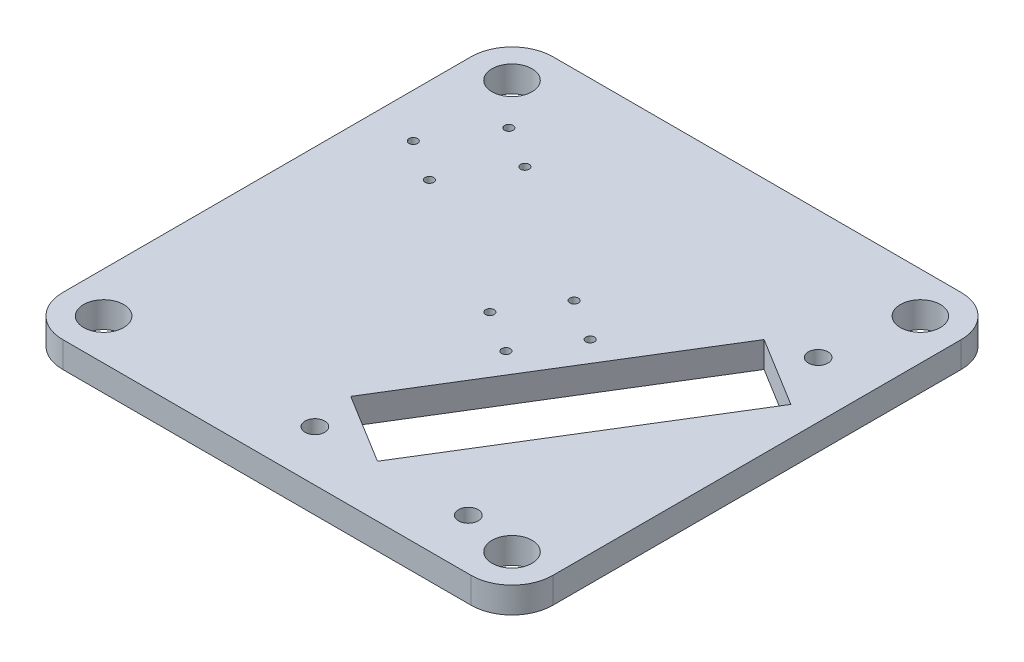
SolidWorks part; units mm, degrees
ref_plane "Front Plane" through (0, 0, 0) normal (0, 0, 1) x (1, 0, 0)
ref_plane "Top Plane" through (0, 0, 0) normal (0, 1, 0) x (1, 0, 0)
ref_plane "Right Plane" through (0, 0, 0) normal (1, 0, 0) x (0, 0, -1)
sketch "Sketch1" plane through (0, 0, 0) normal (0, 1, 0) x (1, 0, 0)
  line L1 (10, 0) -> (110, 0)
  line L2 (0, 10) -> (0, 110)
  line L3 (10, 120) -> (110, 120)
  line L4 (120, 10) -> (120, 110)
  arc A0 (110, 0) -> (120, 10) centre (110, 10) ccw
  arc A1 (10, 0) -> (0, 10) centre (10, 10) cw
  arc A2 (0, 110) -> (10, 120) centre (10, 110) cw
  arc A3 (110, 120) -> (120, 110) centre (110, 110) cw
  point P7 (120, 0)
  point P10 (0, 0)
  point P13 (0, 120)
  point P16 (120, 120)
  dimension "D3" = 10
  dimension "D1" = 120
  dimension "D2" = 120
extrude "Boss-Extrude1" add sketch "Sketch1" along normal blind 6.35
sketch "Sketch2" plane through (0, 6.35, 0) normal (0, 1, 0) x (1, 0, 0)
  line L0 (55.0317, 10) -> (99.0317, 10) construction
  line L1 (99.0317, 10) -> (110, 99.33) construction
  line L2 (110, 99.33) -> (55.0317, 10) construction
  line L3 (110, 120) -> (10, 120) construction
  line L4 (0, 110) -> (0, 10) construction
  line L5 (57.2915, 23.2132) -> (74.325, 12.7318)
  line L6 (74.325, 12.7318) -> (112.886, 75.398)
  line L7 (112.886, 75.398) -> (95.8525, 85.8794)
  line L8 (57.2915, 23.2132) -> (95.8525, 85.8794)
  line L9 (10, 0) -> (110, 0) construction
  line L10 (120, 10) -> (120, 110) construction
  circle A0 centre (59.3264, 12.4) radius 2.4
  circle A1 centre (96.9083, 12.4) radius 2.4
  circle A2 centre (106.2767, 88.6997) radius 2.4
  circle A3 centre (10, 110) radius 4.9
  circle A4 centre (10, 10) radius 4.9
  circle A5 centre (110, 110) radius 4.9
  circle A6 centre (110, 10) radius 4.9
  dimension "D6" = 4.8
  dimension "D7" = 4.8
  dimension "D8" = 4.8
  dimension "D14" = 9.8
  dimension "D15" = 9.8
  dimension "D16" = 9.8
  dimension "D17" = 9.8
  dimension "D20" = 10
  dimension "D1" = 97
  dimension "D2" = 44
  dimension "D3" = 89.33
  dimension "D4" = 10
  dimension "D5" = 10
  dimension "D9" = 20
  dimension "D10" = 73.58
  dimension "D11" = 5
  dimension "D12" = 7.865
  dimension "D13" = 8.1428
  dimension "D18" = 10
  dimension "D19" = 10
  dimension "D21" = 10
  dimension "D22" = 10
  dimension "D23" = 10
  dimension "D24" = 10
  dimension "D25" = 10
extrude "Cut-Extrude1" cut sketch "Sketch2" against normal through all
sketch "Sketch5" plane through (0, 6.35, 0) normal (0, 1, 0) x (1, 0, 0)
  line L0 (76.572, 54.5463) -> (0, 101.6641) construction
  line L1 (95.8525, 85.8794) -> (57.2915, 23.2132) construction
  line L2 (0, 110) -> (0, 10) construction
  circle A0 centre (66.6797, 51.8272) radius 1.05
  circle A1 centre (56.4596, 58.1161) radius 1.05
  circle A2 centre (74.5408, 64.6023) radius 1.05
  circle A3 centre (64.3207, 70.8912) radius 1.05
  circle A4 centre (10.7968, 85.0401) radius 1.05
  circle A5 centre (21.0169, 78.7513) radius 1.05
  circle A6 centre (29.9261, 93.2297) radius 1.05
  circle A7 centre (19.706, 99.5186) radius 1.05
  dimension "D2" = 2.1
  dimension "D3" = 2.1
  dimension "D4" = 2.1
  dimension "D5" = 2.1
  dimension "D14" = 2.1
  dimension "D15" = 2.1
  dimension "D16" = 2.1
  dimension "D17" = 2.1
  dimension "D1" = 90
  dimension "D6" = 7.5
  dimension "D7" = 7.5
  dimension "D8" = 7.5
  dimension "D9" = 7.5
  dimension "D10" = 7
  dimension "D11" = 7
  dimension "D12" = 12
  dimension "D13" = 12
  dimension "D18" = 8.5
  dimension "D19" = 8.5
  dimension "D20" = 8.5
  dimension "D21" = 8.5
  dimension "D22" = 60
  dimension "D23" = 60
  dimension "D24" = 12
  dimension "D25" = 12
extrude "Cut-Extrude2" cut sketch "Sketch5" against normal through all
sketch "Sketch4" plane through (0, 0, 0) normal (0, -1, 0) x (1, 0, 0)
  line L0 (76.572, -54.5463) -> (93.6055, -44.0649) construction
  line L1 (95.8525, -85.8794) -> (57.2915, -23.2132) construction
  line L2 (74.325, -12.7318) -> (112.886, -75.398) construction
